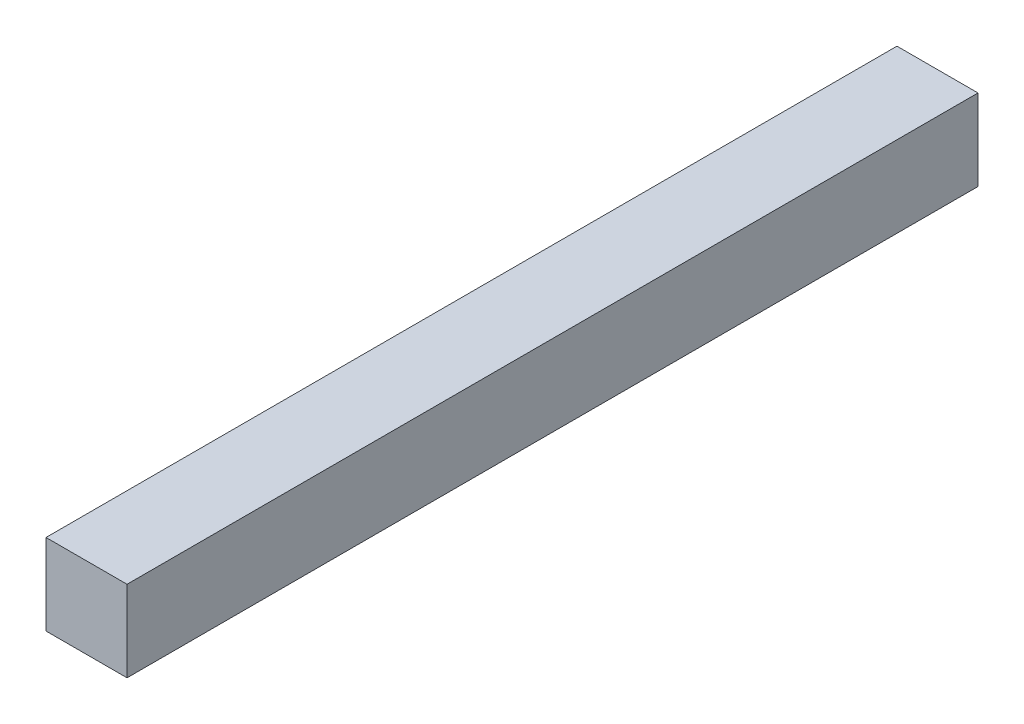
SolidWorks part; units mm, degrees
material "Brass"
ref_plane "Front Plane" through (0, 0, 0) normal (0, 0, 1) x (1, 0, 0)
ref_plane "Top Plane" through (0, 0, 0) normal (0, 1, 0) x (1, 0, 0)
ref_plane "Right Plane" through (0, 0, 0) normal (1, 0, 0) x (0, 0, -1)
sketch "Sketch1" plane through (0, 0, 0) normal (0, 0, 1) x (1, 0, 0)
  line L1 (0, 0) -> (-6.35, 0)
  line L2 (0, 0) -> (0, 6.35)
  line L3 (0, 6.35) -> (-6.35, 6.35)
  line L4 (-6.35, 0) -> (-6.35, 6.35)
  dimension "D1" = 6.35
  dimension "D2" = 6.35
extrude "Boss-Extrude1" add sketch "Sketch1" along normal blind 66.675
